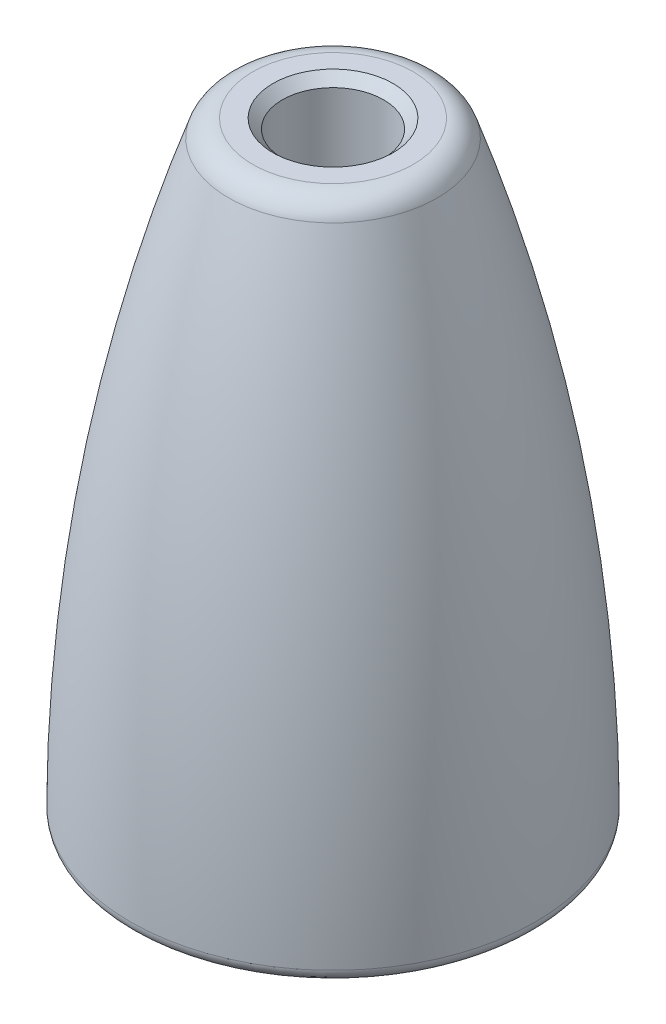
SolidWorks part; units mm, degrees
ref_plane "Front Plane" through (0, 0, 0) normal (0, 0, 1) x (1, 0, 0)
ref_plane "Top Plane" through (0, 0, 0) normal (0, 1, 0) x (1, 0, 0)
ref_plane "Right Plane" through (0, 0, 0) normal (1, 0, 0) x (0, 0, -1)
sketch "Sketch1" plane through (0, 0, 0) normal (1, 0, 0) x (0, 0, -1)
  line L0 (0, 0) -> (0, 11.9029) construction
  line L1 (0, 0) -> (6.35, 0) construction
  line L2 (1.5875, 0.2953) -> (1.5875, 18.7547)
  line L3 (1.8828, 19.05) -> (2.5173, 19.05)
  line L4 (6.35, 0) -> (6.35, 11.9029) construction
  line L5 (1.8828, 0) -> (5.9517, 0)
  line L6 (1.5875, 18.7547) -> (1.8828, 19.05)
  line L7 (1.8828, 0) -> (1.5875, 0.2953)
  arc A0 (3.2683, 18.5134) -> (6.3486, 0.3997) centre (-50.8, 0) cw
  arc A1 (3.2683, 18.5134) -> (2.5173, 19.05) centre (2.5173, 18.2563) ccw
  arc A2 (6.3486, 0.3997) -> (5.9517, 0) centre (5.9517, 0.3969) cw
  point P4 (1.5875, 0)
  point P5 (1.5875, 19.05)
  dimension "D4" = 0.7937
  dimension "D5" = 0.3969
  dimension "D6" = 57.15
  dimension "D1" = 12.7
  dimension "D2" = 3.175
  dimension "D3" = 19.05
  dimension "D8" = 0.2953
  dimension "D9" = 0.2953
revolve "Revolve1" add sketch "Sketch1" angle 360 about L0
scale "Scale1" scale about centroid uniform scaling yes scale factor 0.8
